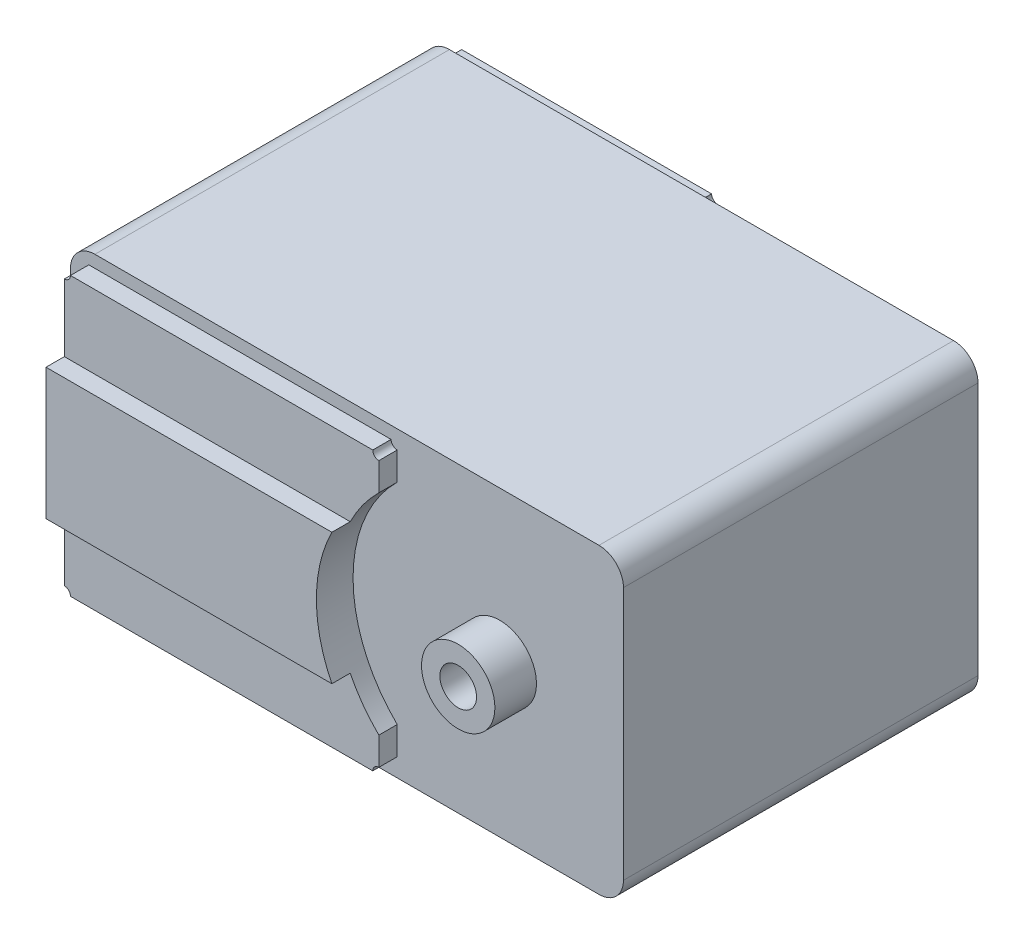
SolidWorks part; units mm, degrees
ref_plane "前视基准面" through (0, 0, 0) normal (0, 0, 1) x (1, 0, 0)
ref_plane "上视基准面" through (0, 0, 0) normal (0, 1, 0) x (1, 0, 0)
ref_plane "右视基准面" through (0, 0, 0) normal (1, 0, 0) x (0, 0, -1)
sketch "草图1" plane through (0, 0, 0) normal (0, 0, 1) x (1, 0, 0)
  line L1 (-22.615, -12.365) -> (22.615, -12.365)
  line L2 (-22.615, -12.365) -> (-22.615, 12.365)
  line L3 (-22.615, 12.365) -> (22.615, 12.365)
  line L4 (22.615, -12.365) -> (22.615, 12.365)
  line L5 (-22.615, -12.365) -> (22.615, 12.365) construction
  line L6 (-22.615, 12.365) -> (22.615, -12.365) construction
  point P0 (0, 0)
  dimension "D1" = 24.73
  dimension "D2" = 45.23
extrude "凸台-拉伸1" add sketch "草图1" along normal blind 29
fillet "圆角1" radius 2 4 edges at (-22.615, 12.365, 14.5) (-22.615, -12.365, 14.5) (22.615, -12.365, 14.5) (22.615, 12.365, 14.5)
sketch "草图2" plane through (0, 0, 29) normal (0, 0, 1) x (1, 0, 0)
  line L0 (22.615, -10.365) -> (22.615, 10.365) construction
  line L1 (20.615, 12.365) -> (-20.615, 12.365) construction
  circle A0 centre (12.5, 0) radius 3
  point P4 (0, 0)
  dimension "D1" = 6
  dimension "D2" = 10.115
  dimension "D3" = 12.365
extrude "凸台-拉伸2" add sketch "草图2" along normal blind 3.4
sketch "草图3" plane through (0, 0, 32.4) normal (0, 0, 1) x (1, 0, 0)
  circle A0 centre (12.5, 0) radius 1.5
extrude "切除-拉伸1" cut sketch "草图3" against normal blind 6
sketch "草图4" plane through (0, 0, 29) normal (0, 0, 1) x (1, 0, 0)
  line L0 (20.615, 12.365) -> (-20.615, 12.365) construction
  line L1 (-21.615, 11.365) -> (4.111, 11.365)
  line L2 (-21.615, 11.365) -> (-21.615, -11.365)
  line L3 (-21.615, -11.365) -> (4.111, -11.365)
  line L4 (4.111, 11.365) -> (4.111, -11.365)
  line L5 (-20.615, -12.365) -> (20.615, -12.365) construction
  line L6 (-22.615, 10.365) -> (-22.615, -10.365) construction
  point P4 (4.111, -10.7071)
  dimension "D1" = 1
  dimension "D2" = 1
  dimension "D3" = 1
extrude "凸台-拉伸3" add sketch "草图4" along normal blind 1.5
sketch "草图5" plane through (0, 0, 30.5) normal (0, 0, 1) x (1, 0, 0)
  circle A0 centre (-21.615, 11.365) radius 0.5
  circle A1 centre (4.111, 11.365) radius 0.5
  circle A2 centre (-21.615, -11.365) radius 0.5
  circle A3 centre (4.111, -11.365) radius 0.5
  point P9 (4.111, -11.365)
  point P11 (-21.615, -11.365)
  point P13 (4.111, 11.365)
extrude "切除-拉伸2" cut sketch "草图5" against normal blind 1.5
sketch "草图6" plane through (0, 0, 30.5) normal (0, 0, 1) x (1, 0, 0)
  line L0 (4.111, -10.865) -> (4.111, 10.865) construction
  line L1 (4.111, -8.5805) -> (4.111, 8.5805)
  arc A1 (4.111, 8.5805) -> (4.111, -8.5805) centre (12.5, 0) ccw
extrude "切除-拉伸3" cut sketch "草图6" against normal blind 1.5
sketch "草图7" plane through (0, 0, 30.5) normal (0, 0, 1) x (1, 0, 0)
  line L0 (-21.615, 5.365) -> (1.7661, 5.365)
  line L1 (-21.615, 10.865) -> (-21.615, -10.865) construction
  line L2 (-21.615, -5.365) -> (1.7661, -5.365)
  line L3 (-21.615, 10.865) -> (-21.615, -10.865) construction
  line L5 (3.611, 11.365) -> (-21.115, 11.365) construction
  line L6 (-21.115, -11.365) -> (3.611, -11.365) construction
  line L7 (-21.615, 5.365) -> (-21.615, -5.365)
  arc A0 (4.111, 8.5805) -> (4.111, -8.5805) centre (12.5, 0) ccw construction
  arc A1 (1.7661, 5.365) -> (1.7661, -5.365) centre (12.5, 0) ccw
  dimension "D1" = 6
  dimension "D2" = 6
extrude "凸台-拉伸4" add sketch "草图7" along normal blind 1.5
sketch "草图21" plane through (-20.6296, 0.9597, 0) normal (0, 0, -1) x (-1, 0, 0)
  line L1 (-20.4534, 10.4053) -> (0.9854, 10.4053)
  line L2 (-20.4534, 10.4053) -> (-20.4534, -12.3247)
  line L3 (-20.4534, -12.3247) -> (0.9854, -12.3247)
  line L4 (0.9854, 10.4053) -> (0.9854, -12.3247)
  line L8 (-41.2446, 11.4053) -> (-0.0146, 11.4053) construction
  line L10 (1.9854, 9.4053) -> (1.9854, -11.3247) construction
  point P4 (4.111, -10.7071)
  dimension "D2" = 1
  dimension "D3" = 1
extrude "凸台-拉伸11" add sketch "草图21" along normal blind 1.5
sketch "草图23" plane through (-20.6296, 0.9597, -1.5) normal (0, 0, -1) x (-1, 0, 0)
  circle A0 centre (-20.4534, 10.4053) radius 0.5
  circle A1 centre (0.9854, 10.4053) radius 0.5
  circle A2 centre (-20.4534, -12.3247) radius 0.5
  circle A3 centre (0.9854, -12.3247) radius 0.5
  point P9 (4.111, -11.365)
  point P11 (-21.615, -11.365)
  point P13 (4.111, 11.365)
extrude "切除-拉伸4" cut sketch "草图23" against normal blind 1.5
sketch "草图24" plane through (0, 0, -1.5) normal (0, 0, -1) x (-1, 0, 0)
  line L0 (0.1762, 10.865) -> (0.1762, -10.865) construction
  line L1 (18.615, 9.365) -> (0.1762, 9.365)
  line L2 (18.615, 9.365) -> (18.615, -9.365)
  line L3 (18.615, -9.365) -> (0.1762, -9.365)
  line L4 (0.1762, 9.365) -> (0.1762, -9.365)
  line L5 (0.6762, -11.365) -> (21.115, -11.365) construction
  line L6 (21.115, 11.365) -> (0.6762, 11.365) construction
  line L7 (21.615, -10.865) -> (21.615, 10.865) construction
  dimension "D1" = 2
  dimension "D2" = 2
  dimension "D3" = 3
extrude "凸台-拉伸12" add sketch "草图24" along normal blind 1.5
fillet "圆角2" radius 2 1 edges at (-0.1762, 0, -3)
sketch "草图25" plane through (0, 0, 0) normal (0, 0, -1) x (-1, 0, 0)
  circle A0 centre (-12.365, 0) radius 3
  point P2 (0, 0)
extrude "凸台-拉伸13" add sketch "草图25" along normal blind 4.1
sketch "草图26" plane through (0, 0, -4.1) normal (0, 0, -1) x (-1, 0, 0)
  circle A0 centre (-12.365, 0) radius 1.5
extrude "切除-拉伸5" cut sketch "草图26" against normal blind 4.1
sketch "草图27" plane through (0, 0, 0) normal (0, 0, -1) x (-1, 0, 0)
  line L0 (20.615, -12.365) -> (-20.615, -12.365) construction
  line L1 (-4.8238, 9.365) -> (-0.8238, 9.365)
  line L2 (-4.8238, 9.365) -> (-4.8238, -9.365)
  line L3 (-4.8238, -9.365) -> (-0.8238, -9.365)
  line L4 (-0.8238, 9.365) -> (-0.8238, -9.365)
  line L5 (-20.615, 12.365) -> (20.615, 12.365) construction
  line L6 (0.1762, 10.865) -> (0.1762, -10.865) construction
  dimension "D1" = 3
  dimension "D2" = 3
  dimension "D3" = 1
  dimension "D4" = 4
extrude "切除-拉伸6" cut sketch "草图27" against normal blind 3
